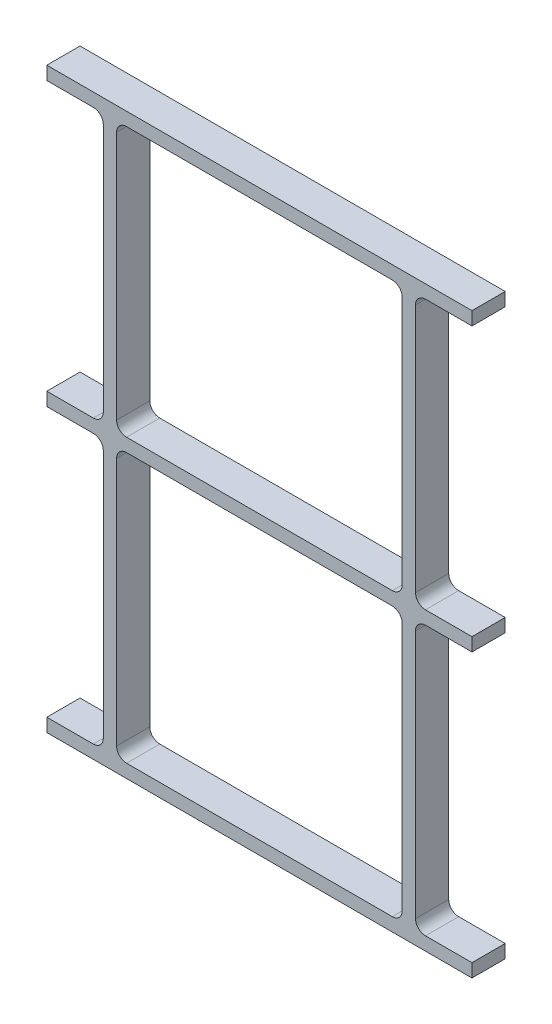
SolidWorks part; units mm, degrees
ref_plane "Front Plane" through (0, 0, 0) normal (0, 0, 1) x (1, 0, 0)
ref_plane "Top Plane" through (0, 0, 0) normal (0, 1, 0) x (1, 0, 0)
ref_plane "Right Plane" through (0, 0, 0) normal (1, 0, 0) x (0, 0, -1)
sketch "Sketch1" plane through (0, 0, 0) normal (0, 0, 1) x (1, 0, 0)
  line L0 (-64, 125.5) -> (-47, 125.5)
  line L5 (-64, 129.5) -> (0, 129.5)
  line L6 (0, -79) -> (0, -42.5) construction
  line L7 (4.5, -79) -> (-4.5, -79) construction
  line L8 (-4.5, 164) -> (4.5, 164) construction
  line L9 (-54, 42.5) -> (-45, 42.5) construction
  line L10 (-54, 63) -> (-54, 22) construction
  line L11 (-54, -42.5) -> (0, -42.5) construction
  line L12 (-54, -22) -> (-54, -63) construction
  line L13 (-43, 44.5) -> (-43, 125.5)
  line L14 (-54, 127.5) -> (0, 127.5) construction
  line L15 (-54, 148) -> (-54, 107) construction
  line L16 (-47, 44.5) -> (-47, 125.5)
  line L17 (-64, 40.5) -> (-47, 40.5)
  line L18 (-45, 42.5) -> (-45, 127.5) construction
  line L19 (-45, 42.5) -> (-45, -42.5) construction
  line L20 (0, 127.5) -> (0, 164) construction
  line L21 (-64, 44.5) -> (-47, 44.5)
  line L22 (-47, 40.5) -> (-47, -40.5)
  line L23 (-43, 40.5) -> (-43, -40.5)
  line L24 (-64, -44.5) -> (0, -44.5)
  line L25 (-64, -40.5) -> (-47, -40.5)
  line L29 (-43, 125.5) -> (43, 125.5)
  line L30 (-54, 40.5) -> (-45, 40.5) construction
  line L31 (-47, 42.5) -> (-47, 127.5) construction
  line L32 (-43, -40.5) -> (43, -40.5)
  line L34 (-54, 125.5) -> (0, 125.5) construction
  line L35 (-43, 42.5) -> (-43, 127.5) construction
  line L39 (45, 42.5) -> (45, -42.5) construction
  line L40 (45, 42.5) -> (45, 127.5) construction
  line L41 (54, 127.5) -> (0, 127.5) construction
  line L42 (54, -42.5) -> (0, -42.5) construction
  line L43 (54, 42.5) -> (45, 42.5) construction
  line L47 (64, -40.5) -> (47, -40.5)
  line L48 (64, -44.5) -> (0, -44.5)
  line L49 (43, 40.5) -> (43, -40.5)
  line L50 (47, 40.5) -> (47, -40.5)
  line L51 (64, 44.5) -> (47, 44.5)
  line L52 (64, 40.5) -> (47, 40.5)
  line L53 (47, 44.5) -> (47, 125.5)
  line L54 (43, 44.5) -> (43, 125.5)
  line L55 (64, 129.5) -> (0, 129.5)
  line L56 (64, 125.5) -> (47, 125.5)
  line L57 (-64, 129.5) -> (-64, 125.5)
  line L58 (64, -44.5) -> (64, -40.5)
  line L59 (64, 125.5) -> (64, 129.5)
  line L60 (64, 40.5) -> (64, 44.5)
  line L61 (-64, -40.5) -> (-64, -44.5)
  line L62 (-64, 44.5) -> (-64, 40.5)
  line L64 (-43, 40.5) -> (43, 40.5)
  line L65 (-43, 44.5) -> (43, 44.5)
  dimension "D3" = 2
extrude "Boss-Extrude1" add sketch "Sketch1" along normal blind 10
fillet "Fillet1" radius 3 16 edges at (43, -40.5, 5) (47, -40.5, 5) (47, 44.5, 5) (43, 44.5, 5) (43, 40.5, 5) (47, 40.5, 5) (47, 125.5, 5) (43, 125.5, 5) (-47, 125.5, 5) (-43, 125.5, 5) (-43, 44.5, 5) (-43, 40.5, 5) (-47, 40.5, 5) (-47, 44.5, 5) (-47, -40.5, 5) (-43, -40.5, 5)
